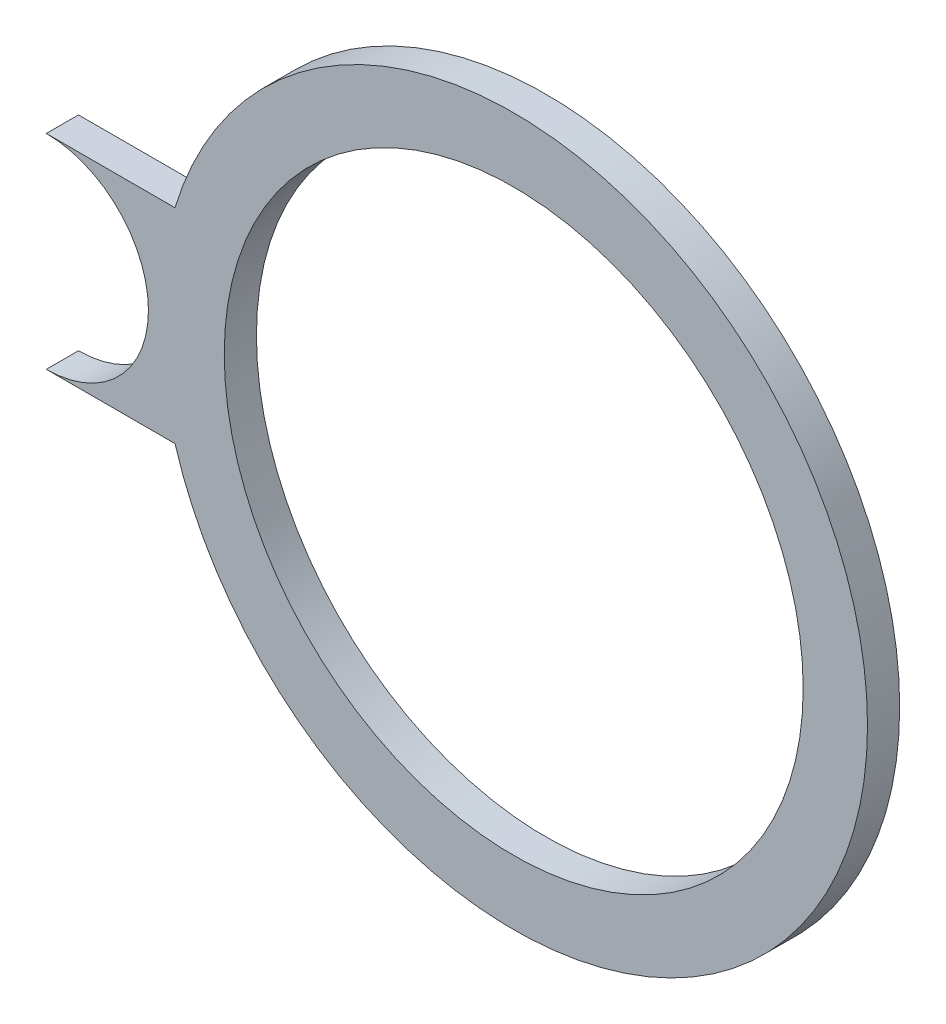
SolidWorks part; units mm, degrees
material "AISI Type 316L stainless steel"
ref_plane "Front Plane" through (0, 0, 0) normal (1, 0, 0) x (0, 1, 0)
ref_plane "Top Plane" through (0, 0, 0) normal (0, 0, 1) x (0, 1, 0)
ref_plane "Right Plane" through (0, 0, 0) normal (0, 1, 0) x (-1, 0, 0)
sketch "Sketch3" plane through (0, 0, 0) normal (0, 0, 1) x (0, 1, 0)
  line L0 (-15.875, 72.6591) -> (-15.875, 52.6591)
  line L1 (-18.4153, 50.5224) -> (-18.1222, 50.5391)
  line L2 (15.875, 52.6591) -> (15.875, 72.6591)
  line L3 (-15.875, 72.6591) -> (15.875, 72.6591) construction
  circle A0 centre (0, 0) radius 45
  arc A1 (-15.875, 52.6591) -> (15.875, 52.6591) centre (0, 0) ccw
  arc A2 (-15.875, 72.6591) -> (15.875, 72.6591) centre (0, 72.6591) ccw
  circle A4 centre (0, 0) radius 55 construction
  point P10 (60, 0)
  dimension "D1" = 90
  dimension "D3" = 31.75
  dimension "D4" = 20
  dimension "D2" = 10
extrude "Boss-Extrude1" add sketch "Sketch3" along normal blind 5 contours A0 | A1 L2 A2 L0
equation "\"roll radius\"= 32mm"
equation "\"rr\"= \"roll radius\""
